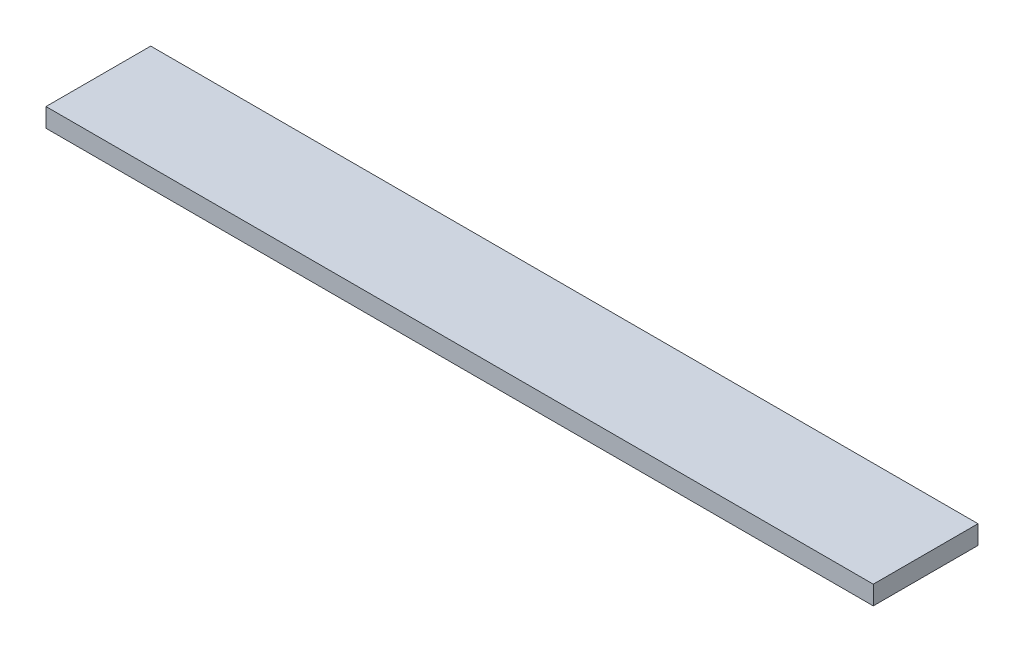
SolidWorks part; units mm, degrees
ref_plane "Front Plane" through (0, 0, 0) normal (0, 0, 1) x (1, 0, 0)
ref_plane "Top Plane" through (0, 0, 0) normal (0, 1, 0) x (1, 0, 0)
ref_plane "Right Plane" through (0, 0, 0) normal (1, 0, 0) x (0, 0, -1)
sketch "Sketch1" plane through (0, 0, 0) normal (0, 1, 0) x (1, 0, 0)
  line L1 (-395, -50) -> (395, -50)
  line L2 (-395, -50) -> (-395, 50)
  line L3 (-395, 50) -> (395, 50)
  line L4 (395, -50) -> (395, 50)
  line L5 (-395, -50) -> (395, 50) construction
  line L6 (-395, 50) -> (395, -50) construction
  point P0 (0, 0)
  dimension "D1" = 790
  dimension "D2" = 100
extrude "Boss-Extrude1" add sketch "Sketch1" along normal blind 18
equation "\"Case_Width\" = 790mm"
equation "\"Case_Depth\" = 470mm"
equation "\"D1@Sketch1\"=\"Case_Width\""
equation "\"Tank_Width\" = 660mm"
equation "\"WoodSheet_Thickness\" = 18mm"
equation "\"D1@Boss-Extrude1\"=\"WoodSheet_Thickness\""
